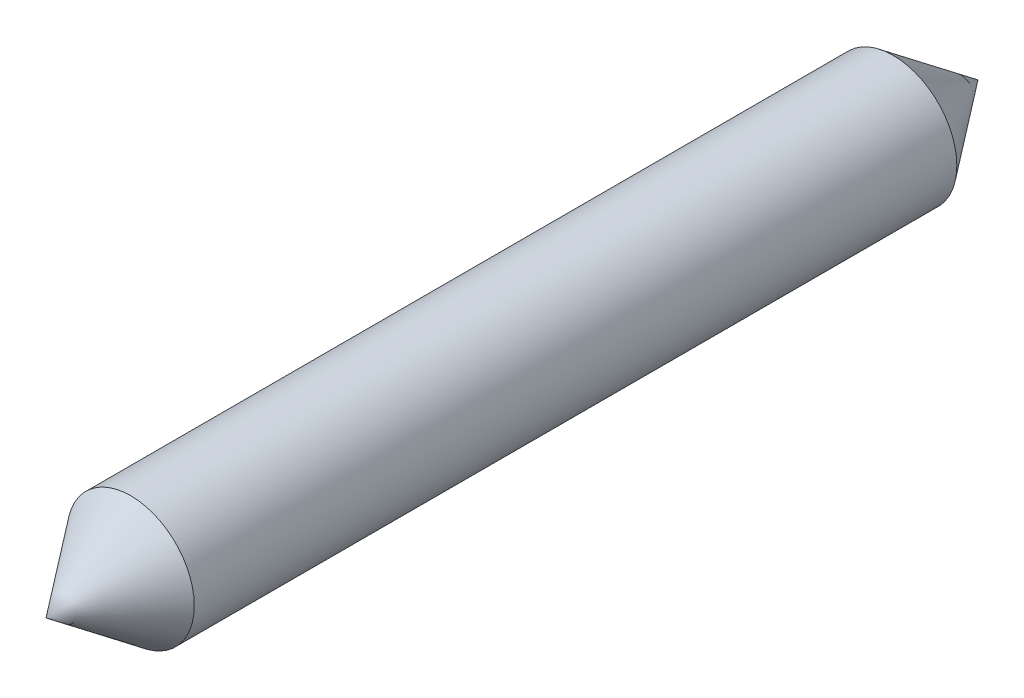
SolidWorks part; units mm, degrees
ref_plane "前视基准面" through (0, 0, 0) normal (0, 0, 1) x (1, 0, 0)
ref_plane "上视基准面" through (0, 0, 0) normal (0, 1, 0) x (1, 0, 0)
ref_plane "右视基准面" through (0, 0, 0) normal (1, 0, 0) x (0, 0, -1)
sketch "草图1" plane through (0, 0, 0) normal (0, 1, 0) x (1, 0, 0)
  line L0 (0, -52.158) -> (0, 66.3094) construction
  line L1 (0, -5.5) -> (0.75, -4.5)
  line L2 (-90.569, 0) -> (86.5257, 0) construction
  line L3 (0.75, -4.5) -> (0.75, 4.5)
  line L4 (0.75, 4.5) -> (0, 5.5)
  line L5 (0, -5.5) -> (0, 5.5)
  dimension "D1" = 0.75
  dimension "D2" = 9
  dimension "D3" = 11
revolve "旋转1" add sketch "草图1" angle 360 about L0
